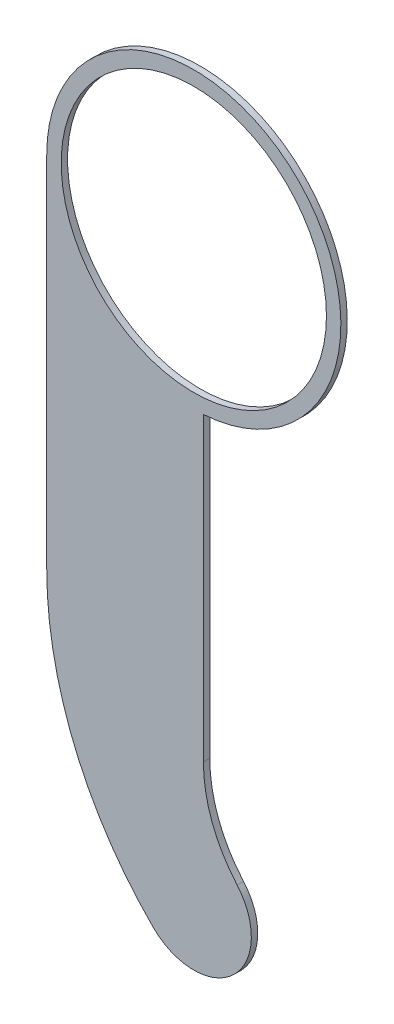
SolidWorks part; units mm, degrees
ref_plane "前视基准面" through (0, 0, 0) normal (0, 0, 1) x (1, 0, 0)
ref_plane "上视基准面" through (0, 0, 0) normal (0, 1, 0) x (1, 0, 0)
ref_plane "右视基准面" through (0, 0, 0) normal (1, 0, 0) x (0, 0, -1)
sketch "草图1" plane through (0, 0, 0) normal (0, 0, 1) x (1, 0, 0)
  line L13 (3, -140.0661) -> (3, -45.9188)
  line L17 (-46.0167, -112.3616) -> (-46.0167, 0)
  circle A6 centre (0, 0) radius 41.5
  arc A19 (-46.0167, 0) -> (3, -45.9188) centre (0, 0) cw
  arc A21 (-12.7279, -192.7279) -> (13.5488, -168.1496) centre (0, -180) ccw
  arc A22 (13.5488, -168.1496) -> (3, -140.0661) centre (45.6573, -140.0661) cw
  arc A23 (-12.7279, -192.7279) -> (-46.0167, -112.3616) centre (67.6384, -112.3616) cw
extrude "凸台-拉伸1" add sketch "草图1" along normal blind 2
